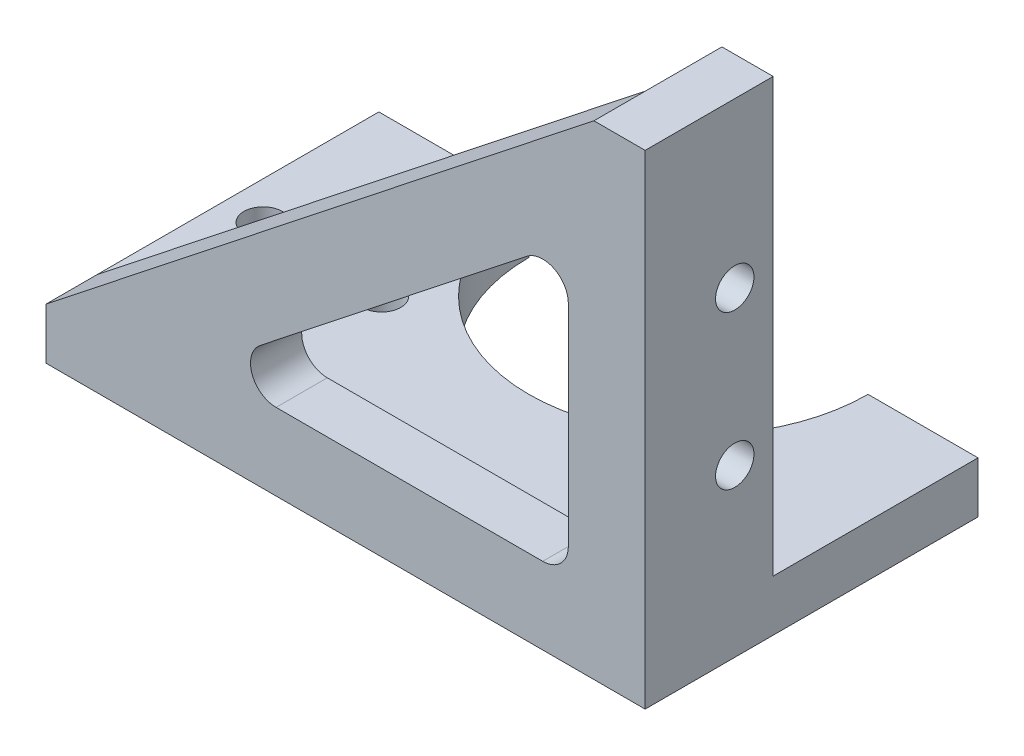
SolidWorks part; units mm, degrees
material "POM 乙缩醛共聚物"
ref_plane "前视基准面" through (0, 0, 0) normal (0, 0, 1) x (1, 0, 0)
ref_plane "上视基准面" through (0, 0, 0) normal (0, 1, 0) x (1, 0, 0)
ref_plane "右视基准面" through (0, 0, 0) normal (1, 0, 0) x (0, 0, -1)
sketch "草图1" plane through (0, 0, 0) normal (0, 0, 1) x (1, 0, 0)
  line L0 (23.4, 2) -> (23.4, 16.0716)
  line L1 (23.4, -2) -> (-23.4, -2)
  line L2 (23.4, -2) -> (23.4, 2)
  line L3 (23.4, 2) -> (-23.4, 2) construction
  line L4 (-23.4, -2) -> (-23.4, 2)
  line L5 (23.4, -2) -> (-23.4, 2) construction
  line L6 (23.4, 2) -> (-23.4, -2) construction
  line L7 (23.4, 35.8) -> (19.4, 35.8)
  line L9 (-23.4, 2) -> (-21.15, 2) construction
  line L10 (19.4, 18.9) -> (23.4, 18.9) construction
  line L11 (19.4, 35.8) -> (19.4, 2)
  line L12 (-16.4, 2) -> (19.4, 2)
  line L13 (23.4, 21.7284) -> (23.4, 35.8)
  line L14 (23.4, 21.7284) -> (23.4, 16.0716)
  line L15 (-23.4, 2) -> (-16.4, 2)
  circle A2 centre (-19.9, 2) radius 1.25 construction
  arc A3 (-16.4, 2) -> (-23.4, 2) centre (-19.9, 2) ccw construction
  circle A4 centre (22.4, 18.9) radius 1 construction
  arc A5 (23.4, 16.0716) -> (23.4, 21.7284) centre (22.4, 18.9) ccw construction
  point P0 (0, 0)
  dimension "D5" = 2
  dimension "D6" = 2.5
  dimension "D8" = 3.5
  dimension "D9" = 6
  dimension "D10" = 3
  dimension "D1" = 4
  dimension "D2" = 4
  dimension "D3" = 37.8
  dimension "D4" = 46.8
extrude "凸台-拉伸1" add sketch "草图1" along normal blind 26
sketch "草图2" plane through (0, 0, 26) normal (0, 0, 1) x (1, 0, 0)
  line L3 (19.4, 2) -> (-23.4, 2) construction
  line L4 (-23.4, 2) -> (-23.4, -2) construction
  line L8 (19.4, 35.8) -> (19.4, 2)
  line L11 (19.4, 2) -> (-23.4, 2)
  line L12 (19.4, 35.8) -> (-23.4, 2)
extrude "凸台-拉伸2" add sketch "草图2" against normal blind 4
sketch "草图3" plane through (0, 2, 0) normal (0, 1, 0) x (1, 0, 0)
  line L0 (19.4, 0) -> (-23.4, 0) construction
  line L1 (23.4, -26) -> (23.4, 0) construction
  line L2 (1.56, 0) -> (13.9344, -12.3744) construction
  line L3 (19.4, 0) -> (-23.4, 0) construction
  circle A0 centre (1.56, 0) radius 17.5 construction
  circle A1 centre (1.56, 0) radius 21 construction
  circle A2 centre (13.9344, -12.3744) radius 1.5
  circle A3 centre (-10.8144, -12.3744) radius 1.5
  circle A4 centre (-10.8144, 12.3744) radius 1.5
  circle A5 centre (13.9344, 12.3744) radius 1.5
  circle A6 centre (1.56, 0) radius 13.25
  circle A7 centre (-20.44, -12) radius 1.5
  point P18 (1.56, 0)
  dimension "D1" = 35
  dimension "D2" = 42
  dimension "D6" = 3
  dimension "D7" = 26.5
  dimension "D10" = 3
  dimension "D3" = 21.84
  dimension "D4" = 45
  dimension "D8" = 22
  dimension "D9" = 12
  dimension "D5" = 4
extrude "切除-拉伸1" cut sketch "草图3" against normal through all
sketch "草图4" plane through (19.4, 0, 0) normal (-1, 0, 0) x (0, 0, 1)
  line L0 (16, 35.8) -> (16, 2)
  line L1 (22, 35.8) -> (0, 35.8) construction
  line L2 (22, 2) -> (0, 2) construction
  line L3 (16, 2) -> (0, 2)
  line L4 (0, 2) -> (0, 35.8)
  line L5 (0, 35.8) -> (16, 35.8)
  line L6 (22, 2) -> (22, 35.8) construction
  dimension "D1" = 6
extrude "切除-拉伸2" cut sketch "草图4" against normal blind 10
sketch "草图5" plane through (19.4, 0, 0) normal (-1, 0, 0) x (0, 0, 1)
  line L0 (19, 35.8) -> (19, 11) construction
  line L1 (22, 35.8) -> (16, 35.8) construction
  line L2 (19, 17) -> (14.177, 17) construction
  line L3 (26, -2) -> (0, -2) construction
  circle A0 centre (19, 23) radius 1.5
  circle A1 centre (19, 11) radius 1.5
  dimension "D1" = 3
  dimension "D2" = 12
  dimension "D3" = 19
extrude "切除-拉伸3" cut sketch "草图5" against normal blind 10
sketch "草图6" plane through (0, 0, 26) normal (0, 0, 1) x (1, 0, 0)
  line L0 (17.4, 26.5752) -> (17.4, 4)
  line L1 (17.4, 4) -> (-11.1863, 4)
  line L2 (-11.1863, 4) -> (17.4, 26.5752)
  line L3 (19.4, 35.8) -> (-23.4, 2) construction
  line L4 (23.4, -2) -> (23.4, 35.8) construction
  line L5 (-23.4, -2) -> (23.4, -2) construction
  dimension "D1" = 6
  dimension "D2" = 6
  dimension "D3" = 6
extrude "切除-拉伸4" cut sketch "草图6" against normal blind 10
fillet "圆角1" radius 2 3 edges at (-11.1863, 4, 24) (17.4, 4, 24) (17.4, 26.5752, 24)
